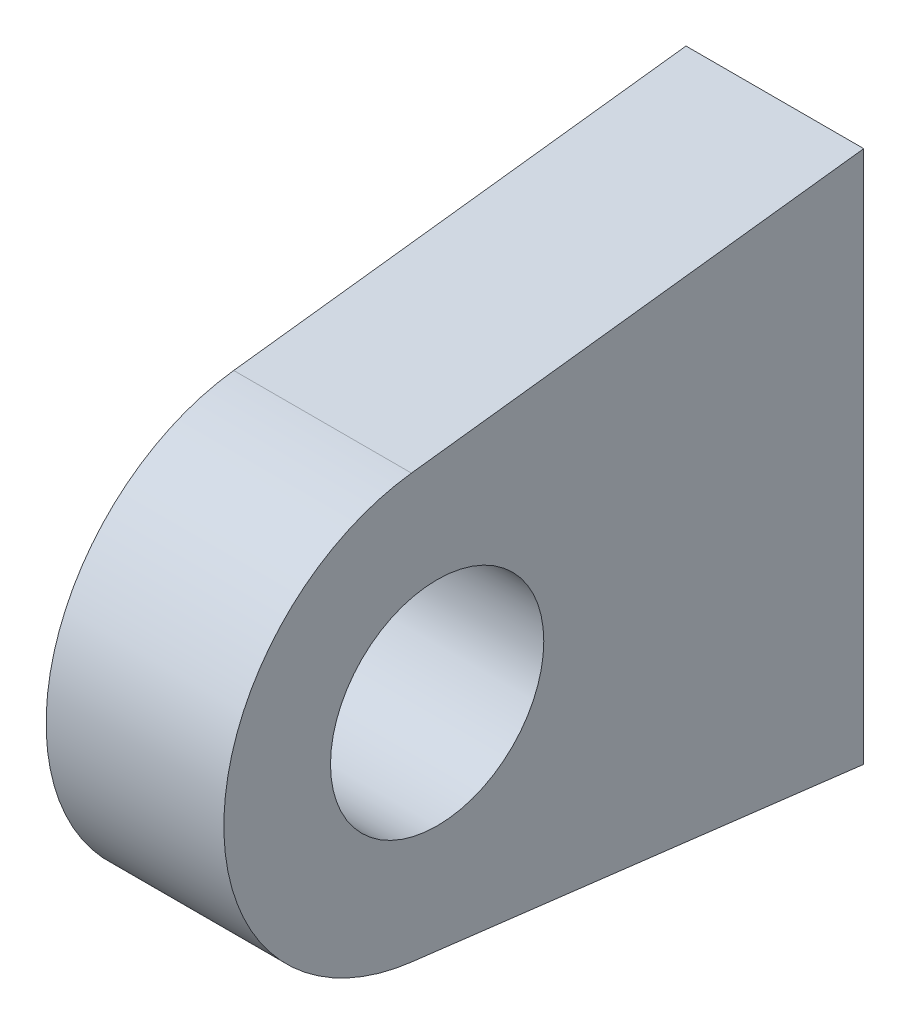
SolidWorks part; units mm, degrees
ref_plane "Front Plane" through (0, 0, 0) normal (1, 0, 0) x (0, 1, 0)
ref_plane "Top Plane" through (0, 0, 0) normal (0, 0, 1) x (0, 1, 0)
ref_plane "Right Plane" through (0, 0, 0) normal (0, 1, 0) x (-1, 0, 0)
sketch "Sketch1" plane through (0, 0, 0) normal (1, 0, 0) x (0, 1, 0)
  line L0 (7.5, 0) -> (-7.5, 0)
  line L1 (0, 0) -> (0, 12)
  line L2 (-7.5, 0) -> (-5.9563, 12.7227)
  line L3 (7.5, 0) -> (5.9563, 12.7227)
  circle A0 centre (0, 12) radius 3
  arc A1 (5.9563, 12.7227) -> (-5.9563, 12.7227) centre (0, 12) ccw
  arc A2 (-5.9563, 12.7227) -> (0, 6) centre (0, 12) ccw construction
  arc A3 (0, 6) -> (5.9563, 12.7227) centre (0, 12) ccw construction
  point P4 (0, 0)
  dimension "D1" = 6
  dimension "D2" = 12
  dimension "D3" = 12
  dimension "D4" = 15
extrude "Boss-Extrude2" add sketch "Sketch1" along normal mid plane 5
